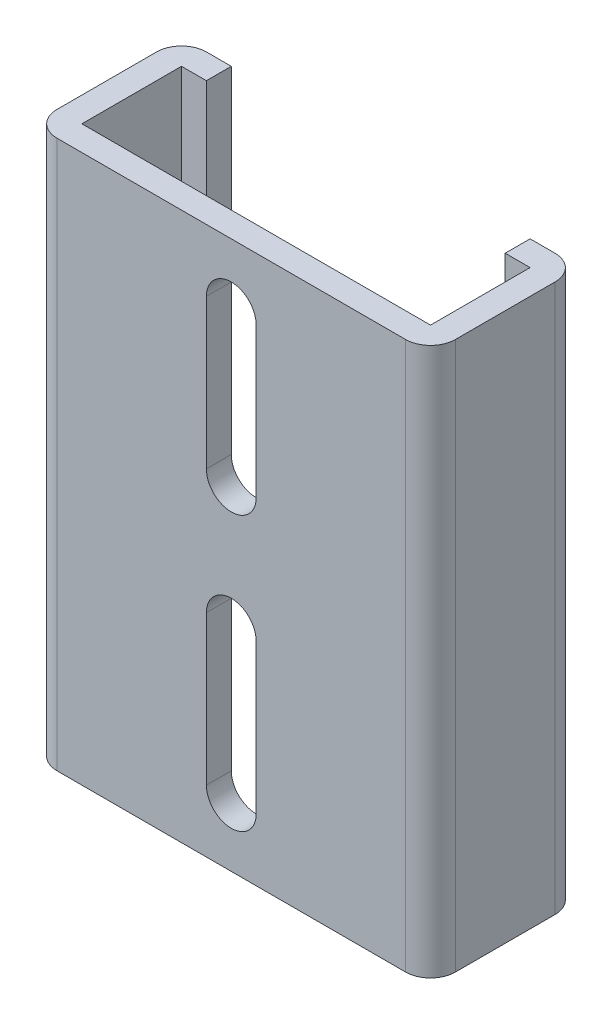
SolidWorks part; units mm, degrees
ref_plane "Front Plane" through (0, 0, 0) normal (0, 0, 1) x (1, 0, 0)
ref_plane "Top Plane" through (0, 0, 0) normal (0, 1, 0) x (1, 0, 0)
ref_plane "Right Plane" through (0, 0, 0) normal (1, 0, 0) x (0, 0, -1)
sketch "Sketch1" plane through (0, 0, 0) normal (0, 1, 0) x (1, 0, 0)
  line L0 (-4, 0) -> (4, 0) construction
  line L1 (4, 0) -> (4, 3) construction
  line L2 (4, 3) -> (3, 3) construction
  line L3 (-3.5, 0) -> (3.5, 0)
  line L4 (4, 0.5) -> (4, 2.5)
  line L5 (3.5, 3) -> (3, 3)
  line L6 (0, 0) -> (0, 1.7551) construction
  line L7 (-4, 3) -> (-3, 3) construction
  line L8 (-4, 0) -> (-4, 3) construction
  line L9 (-3.5, 3) -> (-3, 3)
  line L10 (-4, 0.5) -> (-4, 2.5)
  arc A0 (4, 2.5) -> (3.5, 3) centre (3.5, 2.5) ccw
  arc A1 (3.5, 0) -> (4, 0.5) centre (3.5, 0.5) ccw
  arc A2 (-3.5, 0) -> (-4, 0.5) centre (-3.5, 0.5) cw
  arc A3 (-4, 2.5) -> (-3.5, 3) centre (-3.5, 2.5) cw
  dimension "D3" = 0.5
  dimension "D1" = 4
  dimension "D2" = 3
  dimension "D4" = 0.5
extrude "Extrude-Thin1" add sketch "Sketch1" along normal blind 11 thin
sketch "Sketch3" plane through (0, 0, 0) normal (0, 0, 1) x (1, 0, 0)
  line L0 (0, 5.5) -> (0, 0) construction
  line L1 (3.5, 11) -> (-3.5, 11) construction
  line L2 (0, 5.5) -> (0, 11) construction
  line L3 (0, 0) -> (0, 5.5) construction
  line L4 (0, 9.75) -> (0, 6.75) construction
  line L5 (0, 4.25) -> (0, 1.25) construction
  line L6 (0, 6.75) -> (0, 9.75) construction
  line L7 (-0.5, 6.75) -> (-0.5, 9.75)
  line L8 (0.5, 6.75) -> (0.5, 9.75)
  line L9 (0, 4.25) -> (0, 1.25) construction
  line L10 (0.5, 4.25) -> (0.5, 1.25)
  line L11 (-0.5, 4.25) -> (-0.5, 1.25)
  arc A0 (-0.5, 6.75) -> (0.5, 6.75) centre (0, 6.75) ccw
  arc A1 (0.5, 9.75) -> (-0.5, 9.75) centre (0, 9.75) ccw
  arc A2 (0.5, 4.25) -> (-0.5, 4.25) centre (0, 4.25) ccw
  arc A3 (-0.5, 1.25) -> (0.5, 1.25) centre (0, 1.25) ccw
  point P6 (0, 8.25)
  point P9 (0, 8.25)
  point P12 (0, 2.75)
  point P17 (0, 2.75)
  dimension "D1" = 3
extrude "Cut-Extrude1" cut sketch "Sketch3" against normal blind 1
